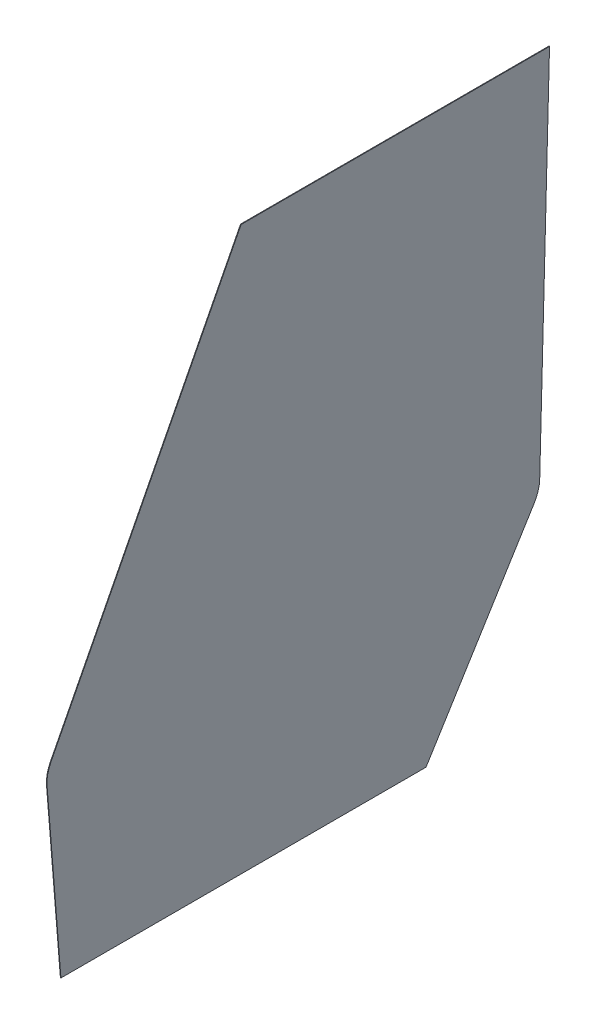
SolidWorks part; units mm, degrees
ref_plane "Front Plane" through (0, 0, 0) normal (0, 0, 1) x (1, 0, 0)
ref_plane "Top Plane" through (0, 0, 0) normal (0, 1, 0) x (1, 0, 0)
ref_plane "Right Plane" through (0, 0, 0) normal (1, 0, 0) x (0, 0, -1)
sketch3d "3DSketch1"
  line L9 (-481.9049, 699.6805, -201.3912) -> (-746.1255, -178.3579, -230)
  line L24 (-718.4398, -568.3409, -190) -> (-718.4398, -568.3409, -215.4)
  line L25 (-718.4398, -568.3409, 190) -> (-718.4398, -568.3409, 215.4)
  line L26 (141.5602, -568.3409, 335) -> (141.5602, -568.3409, 360.4)
  line L27 (141.5602, -568.3409, -335) -> (141.5602, -568.3409, -360.4)
  line L28 (141.5602, -568.3409, 335) -> (227.6317, -163.4064, 446.5558)
  line L29 (141.5602, -568.3409, -335) -> (227.6317, -163.4064, -446.5558)
  line L30 (236.8729, -119.9299, 448.2872) -> (420.1619, 742.3768, 282.9926)
  line L31 (236.8729, -119.9299, -448.2872) -> (420.1619, 742.3768, -282.9926)
  line L32 (420.1619, 742.3768, -282.9926) -> (420.1619, 742.3768, 282.9926)
  line L34 (420.1619, 742.3768, 200) -> (-424.4474, 742.3768, 200)
  line L35 (420.1619, 742.3768, -200) -> (-424.4474, 742.3768, -200)
  line L38 (-746.1255, -178.3579, -230) -> (-718.4398, -568.3409, -190)
  line L39 (-746.1255, -178.3579, 230) -> (-718.4398, -568.3409, 190)
  line L40 (-1178.4398, -568.3409, 190) -> (-718.4398, -568.3409, 190)
  line L41 (-1178.4398, -568.3409, -190) -> (-718.4398, -568.3409, -190)
  line L42 (-718.4398, -568.3409, 190) -> (141.5602, -568.3409, 335)
  line L43 (-718.4398, -568.3409, -190) -> (141.5602, -568.3409, -335)
  line L44 (141.5602, -568.3409, -335) -> (141.5602, -568.3409, 335)
  line L45 (-718.4398, -568.3409, -190) -> (-718.4398, -568.3409, 190)
  line L46 (-1178.4398, -568.3409, -190) -> (-1178.4398, -568.3409, 190)
  line L47 (-1182.0731, -178.3579, -250) -> (-1182.0731, -178.3579, 250)
  line L48 (-481.9049, 699.6805, 201.3912) -> (-746.1255, -178.3579, 230)
  line L51 (-379.8381, 742.3768, -200) -> (-379.8381, 742.3768, 200)
  line L52 (420.1619, 742.3768, 200) -> (420.1619, 742.3768, 282.9926)
  line L53 (420.1619, 742.3768, 282.9926) -> (403.2023, 662.5882, 298.2872)
  line L54 (420.1619, 742.3768, -282.9926) -> (403.2023, 662.5882, -298.2872)
  line L55 (420.1619, 742.3768, -200) -> (420.1619, 742.3768, -282.9926)
  line L56 (-746.1255, -178.3579, -230) -> (-746.1255, -178.3579, 230)
  line L57 (-746.1255, -178.3579, 230) -> (-746.1255, -178.3579, 261.75)
  line L58 (-746.1255, -178.3579, -230) -> (-746.1255, -178.3579, -261.75)
  arc A4 (-481.9049, 699.6805, 201.3912) -> (-424.4474, 742.3768, 200) centre (-424.4474, 682.4087, 201.9539) ccw
  arc A5 (-481.9049, 699.6805, -201.3912) -> (-424.4474, 742.3768, -200) centre (-424.4474, 682.4087, -201.9539) ccw
  arc A6 (227.6317, -163.4064, 446.5558) -> (236.8729, -119.9299, 448.2872) centre (233.0413, -137.956, 350) ccw
  arc A7 (236.8729, -119.9299, -448.2872) -> (227.6317, -163.4064, -446.5558) centre (233.0413, -137.956, -350) ccw
  arc A8 (403.2023, 662.5882, 298.2872) -> (420.1619, 742.3768, 200) centre (399.3707, 644.5621, 200) ccw
  arc A9 (420.1619, 742.3768, -200) -> (403.2023, 662.5882, -298.2872) centre (399.3707, 644.5621, -200) ccw
  point P38 (135.2266, -117.1648, 350)
  point P39 (135.2266, -117.1648, -350)
  point P40 (301.5559, 665.3533, 200)
  point P41 (301.5559, 665.3533, -200)
  point P53 (-469.0567, 742.3768, 200)
  point P55 (-424.4474, 680.4547, 141.9857)
  point P58 (-469.0567, 742.3768, -200)
  point P59 (-424.4474, 684.3626, -261.9221)
  dimension "D1" = 60
  dimension "D2" = 31.75
ref_plane "Plane2" through (251.0235, -53.3567, 0) normal (0.9781, -0.2079, 0) x (0, 0, -1)
sketch "Sketch2" plane through (251.0235, -53.3567, 0) normal (0.9781, -0.2079, 0) x (0, 0, -1)
  line L0 (-448.2872, -68.0605) -> (-282.9926, 813.5107) construction
  line L1 (282.9926, 813.5107) -> (-282.9926, 813.5107) construction
  line L2 (448.2872, -68.0605) -> (282.9926, 813.5107) construction
  line L3 (335, -526.4893) -> (446.5558, -112.5083) construction
  line L4 (335, -526.4893) -> (-335, -526.4893) construction
  line L5 (-335, -526.4893) -> (-446.5558, -112.5083) construction
  line L6 (-448.2872, -68.0605) -> (-282.9926, 813.5107)
  line L7 (282.9926, 813.5107) -> (-282.9926, 813.5107)
  line L8 (448.2872, -68.0605) -> (282.9926, 813.5107)
  line L9 (335, -526.4893) -> (446.5558, -112.5083)
  line L10 (335, -526.4893) -> (-335, -526.4893)
  line L11 (-335, -526.4893) -> (-446.5558, -112.5083)
  arc A0 (-448.2872, -68.0605) -> (-446.5558, -112.5083) centre (-350, -86.4893) ccw construction
  arc A1 (446.5558, -112.5083) -> (448.2872, -68.0605) centre (350, -86.4893) ccw construction
  arc A2 (-448.2872, -68.0605) -> (-446.5558, -112.5083) centre (-350, -86.4893) ccw
  arc A3 (446.5558, -112.5083) -> (448.2872, -68.0605) centre (350, -86.4893) ccw
extrude "Boss-Extrude1" add sketch "Sketch2" along normal blind 1
